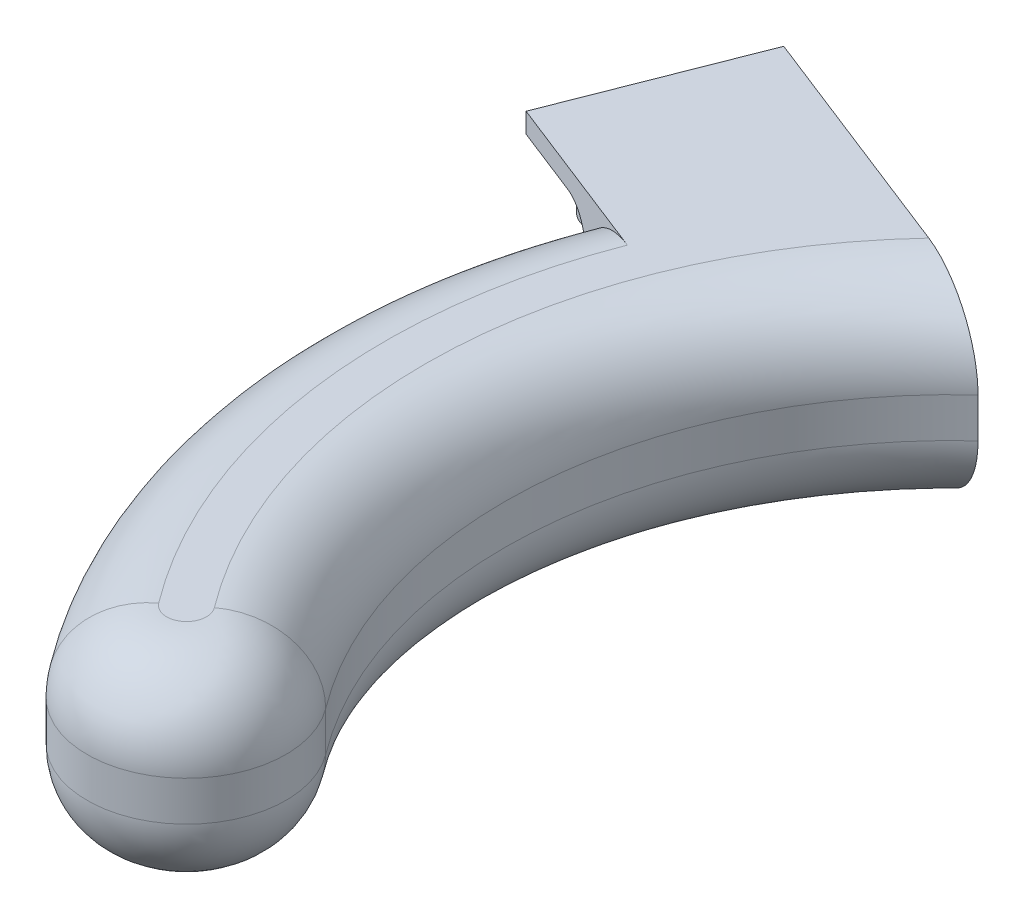
SolidWorks part; units mm, degrees
ref_plane "Front Plane" through (0, 0, 0) normal (0, 0, 1) x (1, 0, 0)
ref_plane "Top Plane" through (0, 0, 0) normal (0, 1, 0) x (1, 0, 0)
ref_plane "Right Plane" through (0, 0, 0) normal (1, 0, 0) x (0, 0, -1)
sketch "Sketch1" plane through (0, 0, 0) normal (0, 1, 0) x (1, 0, 0)
  line L5 (-30.4838, 33.1019) -> (-50.4838, 40.9437)
  arc A3 (-50.4838, 40.9437) -> (-51.9577, -39.0563) centre (0, 0) ccw
  arc A4 (-51.9577, -39.0563) -> (-35.9707, -27.039) centre (-43.9642, -33.0476) ccw
  arc A5 (-35.9707, -27.039) -> (-30.4838, 33.1019) centre (0, 0) cw
  point P8 (0, 0)
  dimension "D2" = 20
  dimension "D3" = 65
  dimension "D1" = 80
  dimension "D4" = 20
extrude "Boss-Extrude1" add sketch "Sketch1" along normal blind 20
sketch "Sketch2" plane through (0, 20, 0) normal (0, 1, 0) x (1, 0, 0)
  line L0 (-39.3615, 36.5828) -> (-62.6364, 45.7086)
  line L1 (-62.6364, 45.7086) -> (-69.937, 27.0887)
  line L2 (-69.937, 27.0887) -> (-51.3171, 19.7881)
  line L3 (-51.3171, 19.7881) -> (-39.3615, 36.5828)
  line L4 (-30.4838, 33.1019) -> (-50.4838, 40.9437) construction
  arc A1 (-50.4838, 40.9437) -> (-51.9577, -39.0563) centre (0, 0) ccw construction
  point P2 (0, 0)
  point P6 (-60.6271, 23.4384)
  point P10 (-50.9989, 41.1457)
  dimension "D1" = 20
  dimension "D2" = 25
  dimension "D3" = 20
fillet "Fillet4" radius 8 6 edges at (-64.989, 0, -1.1974) (-44.8139, 0, -4.0886) (-64.989, 20, -1.1974) (-44.8139, 20, -4.0886) (-37.9556, 0, 41.0411) (-37.9556, 20, 41.0411)
shell "Shell4" thickness 2
extrude "Boss-Extrude3" add sketch "Sketch2" against normal blind 2
fillet "Fillet5" radius 3 1 edges at (-53.6829, 18, -31.5972)
sketch "Sketch4" plane through (0, 18, 0) normal (0, -1, 0) x (1, 0, 0)
  line L0 (-59.8066, -39.2285) -> (-63.4569, -29.9185) construction
  line L1 (-62.6364, -45.7086) -> (-69.937, -27.0887) construction
  line L2 (-53.0023, -41.9312) -> (-62.6364, -45.7086) construction
  circle A0 centre (-59.8066, -39.2285) radius 3
  circle A1 centre (-63.4569, -29.9185) radius 3
  point P10 (-50.8087, -40.8382)
  dimension "D2" = 6
  dimension "D3" = 6
  dimension "D1" = 10
  dimension "D4" = 5
  dimension "D5" = 5
extrude "Boss-Extrude4" add sketch "Sketch4" along normal blind 5
